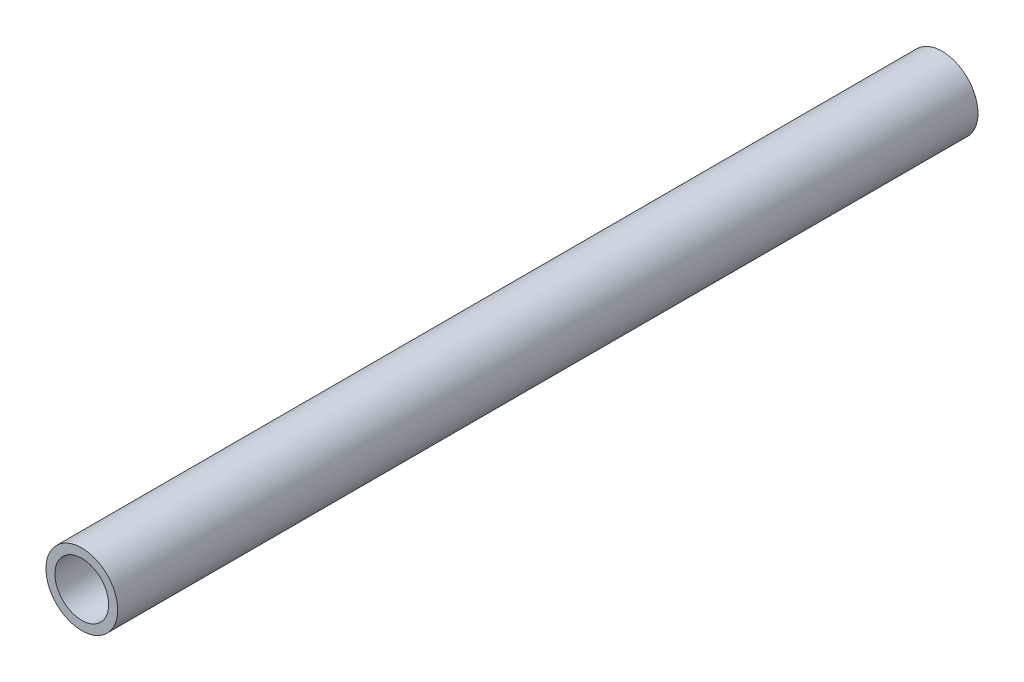
SolidWorks part; units mm, degrees
material "合金钢"
ref_plane "前视基准面" through (0, 0, 0) normal (0, 0, 1) x (1, 0, 0)
ref_plane "上视基准面" through (0, 0, 0) normal (0, 1, 0) x (1, 0, 0)
ref_plane "右视基准面" through (0, 0, 0) normal (1, 0, 0) x (0, 0, -1)
sketch "草图1" plane through (0, 0, 0) normal (0, 0, 1) x (1, 0, 0)
  circle A0 centre (0, 0) radius 4
  dimension "D1" = 8
extrude "凸台-拉伸1" add sketch "草图1" along normal mid plane 96
sketch "草图2" plane through (0, 0, 48) normal (0, 0, 1) x (1, 0, 0)
  circle A0 centre (0, 0) radius 3
  dimension "D1" = 6
extrude "切除-拉伸1" cut sketch "草图2" against normal blind 100
